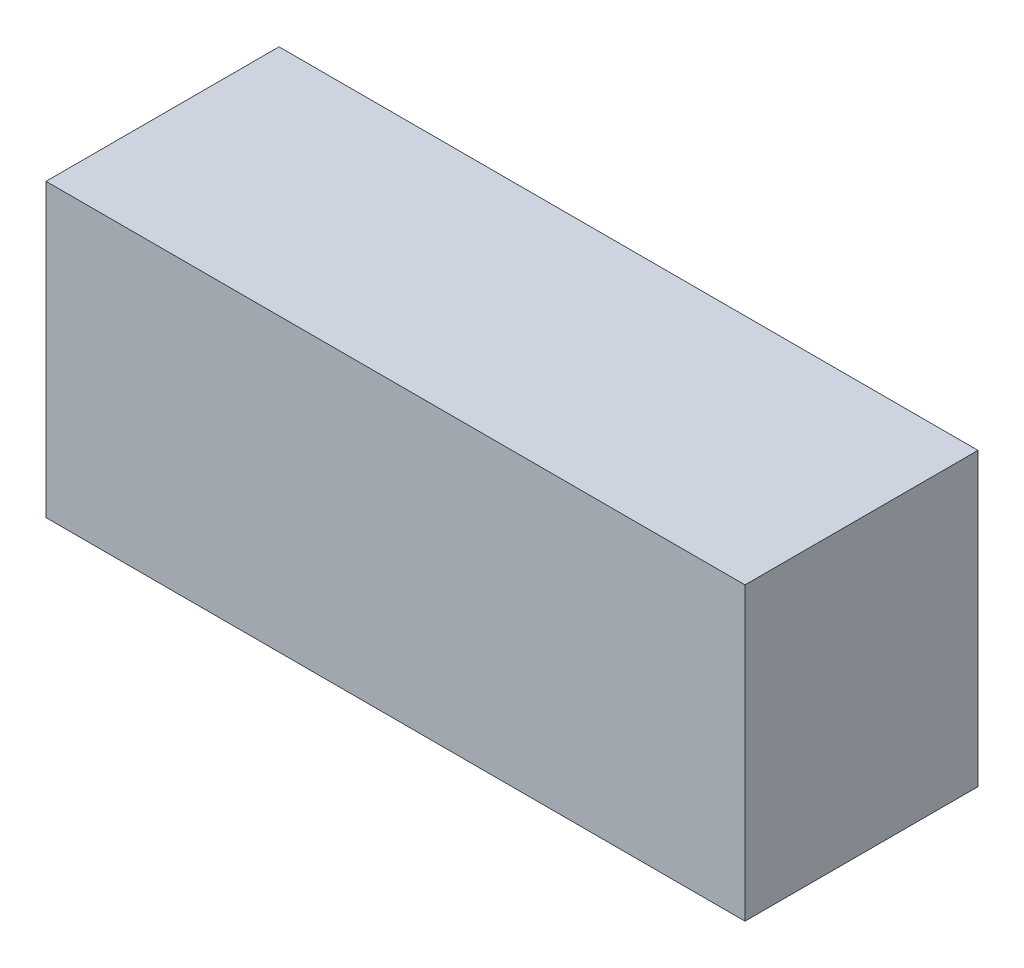
SolidWorks part; units mm, degrees
ref_plane "Front Plane" through (0, 0, 0) normal (0, 0, 1) x (1, 0, 0)
ref_plane "Top Plane" through (0, 0, 0) normal (0, 1, 0) x (1, 0, 0)
ref_plane "Right Plane" through (0, 0, 0) normal (1, 0, 0) x (0, 0, -1)
sketch "Sketch1" plane through (0, 0, 0) normal (0, 1, 0) x (1, 0, 0)
  line L1 (-19.05, -6.35) -> (19.05, -6.35)
  line L2 (-19.05, -6.35) -> (-19.05, 6.35)
  line L3 (-19.05, 6.35) -> (19.05, 6.35)
  line L4 (19.05, -6.35) -> (19.05, 6.35)
  line L5 (-19.05, -6.35) -> (19.05, 6.35) construction
  line L6 (-19.05, 6.35) -> (19.05, -6.35) construction
  point P0 (0, 0)
  dimension "D1" = 38.1
  dimension "D2" = 12.7
extrude "Boss-Extrude1" add sketch "Sketch1" along normal blind 15.875
